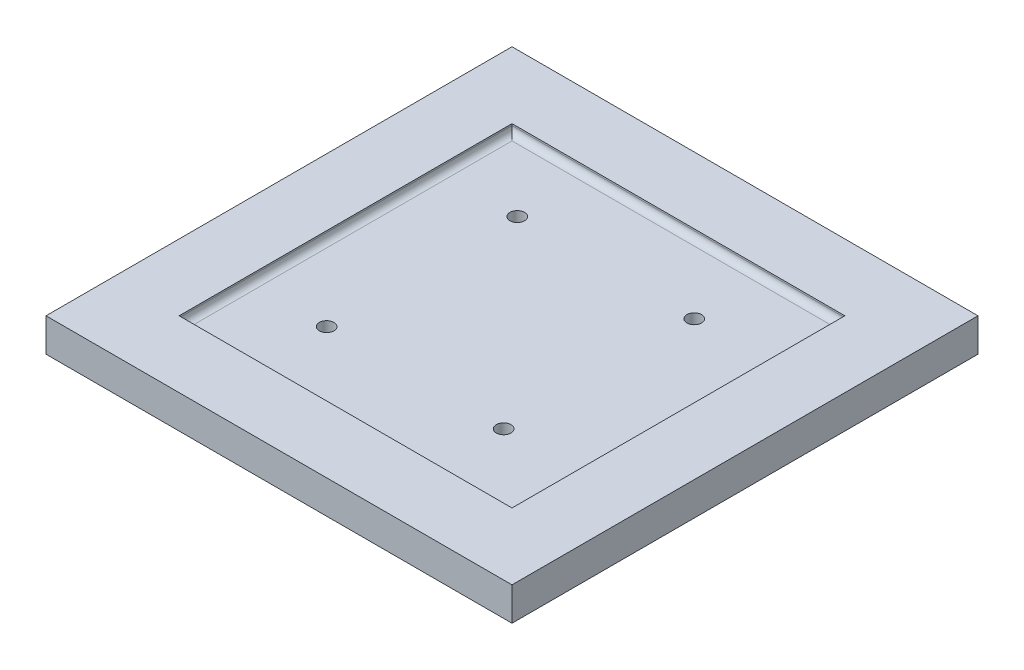
SolidWorks part; units mm, degrees
ref_plane "Front Plane" through (0, 0, 0) normal (0, 0, 1) x (1, 0, 0)
ref_plane "Top Plane" through (0, 0, 0) normal (0, 1, 0) x (1, 0, 0)
ref_plane "Right Plane" through (0, 0, 0) normal (1, 0, 0) x (0, 0, -1)
sketch "Sketch10" plane through (0, 0, 0) normal (0, 1, 0) x (1, 0, 0)
  line L1 (88.9, -88.9) -> (-88.9, -88.9)
  line L2 (88.9, -88.9) -> (88.9, 88.9)
  line L3 (88.9, 88.9) -> (-88.9, 88.9)
  line L4 (-88.9, -88.9) -> (-88.9, 88.9)
  line L5 (88.9, -88.9) -> (-88.9, 88.9) construction
  line L6 (88.9, 88.9) -> (-88.9, -88.9) construction
  point P0 (0, 0)
  dimension "D1" = 177.8
  dimension "D2" = 177.8
extrude "Boss-Extrude4" add sketch "Sketch10" along normal blind 12.7 contours L2 L1 L4 L3
sketch "Sketch12" plane through (0, 12.7, 0) normal (0, 1, 0) x (1, 0, 0)
  line L1 (63.5, -63.5) -> (-63.5, -63.5)
  line L2 (63.5, -63.5) -> (63.5, 63.5)
  line L3 (63.5, 63.5) -> (-63.5, 63.5)
  line L4 (-63.5, -63.5) -> (-63.5, 63.5)
  line L5 (63.5, -63.5) -> (-63.5, 63.5) construction
  line L6 (63.5, 63.5) -> (-63.5, -63.5) construction
  point P1 (0, 0)
  dimension "D1" = 127
  dimension "D2" = 127
extrude "Boss-Extrude5" add sketch "Sketch12" against normal blind 3.175
sketch "Sketch13" plane through (0, 12.7, 0) normal (0, 1, 0) x (1, 0, 0)
  line L1 (63.5, -63.5) -> (-63.5, -63.5)
  line L2 (63.5, -63.5) -> (63.5, 63.5)
  line L3 (63.5, 63.5) -> (-63.5, 63.5)
  line L4 (-63.5, -63.5) -> (-63.5, 63.5)
  line L5 (63.5, -63.5) -> (-63.5, 63.5) construction
  line L6 (63.5, 63.5) -> (-63.5, -63.5) construction
  point P0 (0, 0)
  dimension "D1" = 127
  dimension "D2" = 127
extrude "Cut-Extrude1" cut sketch "Sketch13" against normal blind 3.175
sketch "Sketch14" plane through (0, 0, 0) normal (0, -1, 0) x (-1, 0, 0)
  line L1 (63.5, -63.5) -> (-63.5, -63.5)
  line L2 (63.5, -63.5) -> (63.5, 63.5)
  line L3 (63.5, 63.5) -> (-63.5, 63.5)
  line L4 (-63.5, -63.5) -> (-63.5, 63.5)
  line L5 (63.5, -63.5) -> (-63.5, 63.5) construction
  line L6 (63.5, 63.5) -> (-63.5, -63.5) construction
  point P0 (0, 0)
  dimension "D1" = 127
  dimension "D2" = 127
extrude "Cut-Extrude2" cut sketch "Sketch14" against normal blind 3.175
fillet "Fillet4" radius 2.54 8 edges at (-63.5, 9.525, 0) (0, 9.525, 63.5) (0, 9.525, -63.5) (63.5, 9.525, 0) (0, 3.175, 63.5) (-63.5, 3.175, 0) (0, 3.175, -63.5) (63.5, 3.175, 0)
sketch "Sketch16" plane through (0, 9.525, 0) normal (0, 1, 0) x (1, 0, 0)
  circle A0 centre (-34.9456, 36.9526) radius 2.794
  circle A1 centre (32.5844, 36.9526) radius 2.794
  circle A2 centre (-34.9456, -35.772) radius 2.794
  circle A3 centre (32.5844, -35.772) radius 2.794
  dimension "D1" = 5.588
extrude "Cut-Extrude3" cut sketch "Sketch16" against normal blind 25.4
